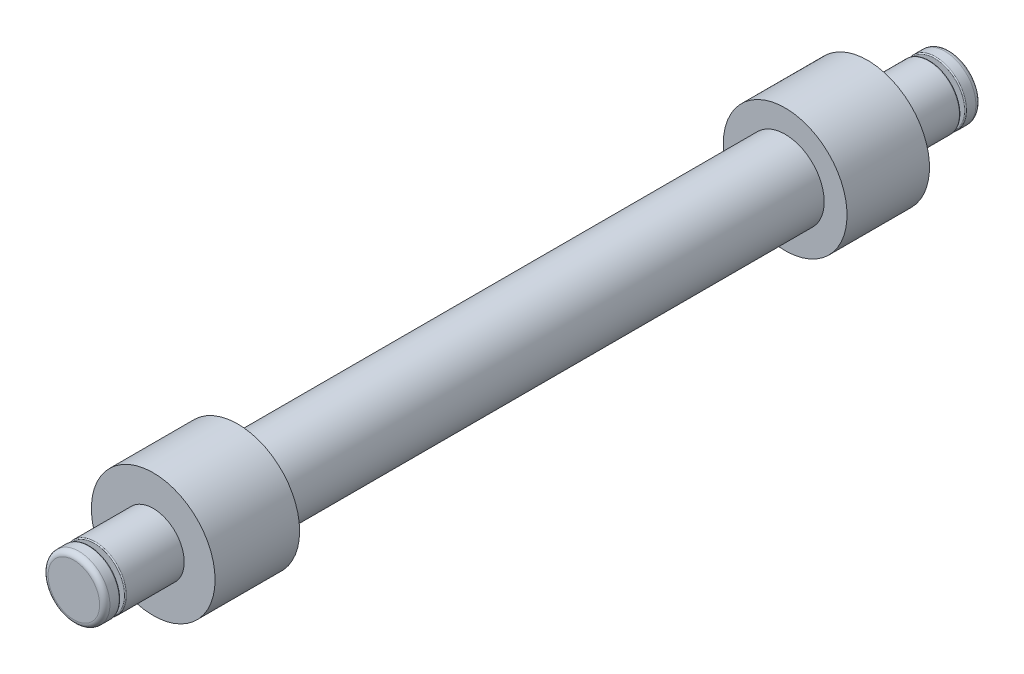
SolidWorks part; units mm, degrees
ref_plane "Front Plane" through (0, 0, 0) normal (0, 0, 1) x (1, 0, 0)
ref_plane "Top Plane" through (0, 0, 0) normal (0, 1, 0) x (1, 0, 0)
ref_plane "Right Plane" through (0, 0, 0) normal (1, 0, 0) x (0, 0, -1)
sketch "Sketch1" plane through (0, 0, 0) normal (0, 0, 1) x (1, 0, 0)
  circle A0 centre (-146.1513, 83.7635) radius 3.7849 construction
  circle A1 centre (-146.1513, 83.7635) radius 3.7849
extrude "Boss-Extrude1" add sketch "Sketch1" against normal blind 55.1
sketch "Sketch2" plane through (0, 0, 0) normal (0, 0, 1) x (1, 0, 0)
  circle A0 centre (-146.1513, 83.7635) radius 6
  dimension "D1" = 12
extrude "Boss-Extrude2" add sketch "Sketch2" along normal blind 6.2 and the other way blind 2
sketch "Sketch3" plane through (0, 0, -55.1) normal (0, 0, -1) x (-1, 0, 0)
  circle A0 centre (146.1513, 83.7635) radius 6
  dimension "D1" = 12
extrude "Boss-Extrude3" add sketch "Sketch3" along normal blind 8
sketch "Sketch4" plane through (0, 0, -63.1) normal (0, 0, -1) x (-1, 0, 0)
  circle A0 centre (146.1513, 83.7635) radius 3.0039
extrude "Boss-Extrude4" add sketch "Sketch4" along normal blind 6 and the other way blind 75
sketch "Sketch5" plane through (0, 0, -69.1) normal (0, 0, -1) x (-1, 0, 0)
  circle A0 centre (146.1513, 83.7635) radius 1.75
  dimension "D1" = 3.5
extrude "Boss-Extrude5" add sketch "Sketch5" along normal blind 0.5 and the other way blind 81.5
sketch "Sketch6" plane through (0, 0, -69.6) normal (0, 0, -1) x (-1, 0, 0)
  circle A0 centre (146.1513, 83.7635) radius 3.0039
extrude "Boss-Extrude6" add sketch "Sketch6" along normal blind 1.5
sketch "Sketch7" plane through (0, 0, 12.4) normal (0, 0, 1) x (1, 0, 0)
  circle A0 centre (-146.1513, 83.7635) radius 3
  dimension "D1" = 6
extrude "Boss-Extrude7" add sketch "Sketch7" along normal blind 1.5
fillet "Fillet1" radius 0.5 2 edges at (-149.1552, 83.7635, -71.1) (-143.1513, 83.7635, 13.9)
fillet "Fillet2" radius 0.1 4 edges at (-143.1513, 83.7635, 12.4) (-149.1552, 83.7635, 11.9) (-149.1552, 83.7635, -69.6) (-149.1552, 83.7635, -69.1)
